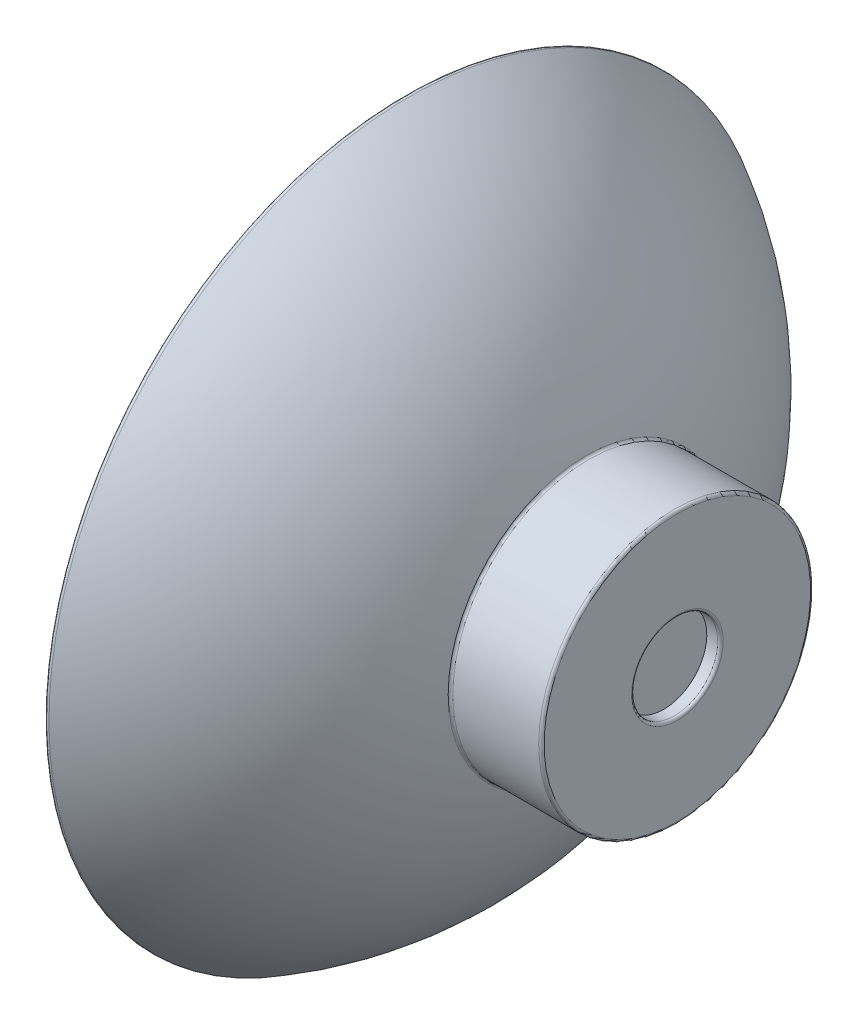
SolidWorks part; units mm, degrees
ref_plane "Front Plane" through (0, 0, 0) normal (0, 0, 1) x (1, 0, 0)
ref_plane "Top Plane" through (0, 0, 0) normal (0, 1, 0) x (1, 0, 0)
ref_plane "Right Plane" through (0, 0, 0) normal (1, 0, 0) x (0, 0, -1)
sketch "Sketch1" plane through (0, 0, 0) normal (0, 0, 1) x (1, 0, 0)
  line L0 (0, 0) -> (0, 7.5)
  line L1 (0, 7.5) -> (5, 7.5)
  line L2 (5, 7.5) -> (5, 0)
  line L4 (2, 0) -> (2, 4.75)
  line L5 (2, 4.75) -> (4, 4.75)
  line L6 (4, 4.75) -> (4, 0)
  line L7 (0, 0) -> (-10, 0) construction
  line L8 (-10, 0) -> (-10, 20) construction
  line L9 (-10, 18.822) -> (-15, 18.822)
  line L10 (-10, 20) -> (-10, 18.822)
  line L11 (4, 0) -> (5, 0)
  line L12 (0, 0) -> (6.4665, 0) construction
  line L13 (4.9087, 0) -> (6.4665, 0) construction
  line L14 (0, 0) -> (5, 0)
  arc A0 (0, 7.5) -> (-10, 20) centre (-19.3122, 2.3002) ccw
  arc A1 (-10, 18.822) -> (0, 4) centre (-21.6638, 0.1684) cw
  dimension "D8" = 5
  dimension "D10" = 22
  dimension "D1" = 5
  dimension "D2" = 7.5
  dimension "D3" = 2
  dimension "D4" = 1
  dimension "D6" = 10
  dimension "D7" = 20
  dimension "D9" = 3.5
revolve "Revolve3" add sketch "Sketch1" angle 360 about L7
sketch "Sketch2" plane through (5, 0, 0) normal (1, 0, 0) x (0, 0, -1)
  circle A0 centre (0, 0) radius 2.375
extrude "Cut-Extrude2" cut sketch "Sketch2" against normal blind 0.75 contours A0
fillet "Fillet1" radius 0.15 4 edges at (-10, 18.822, 0) (0, 4, 0) (0, 7.5, 0) (5, 7.5, 0)
fillet "Fillet2" radius 0.15 2 edges at (-10, 20, 0) (5, 2.375, 0)
